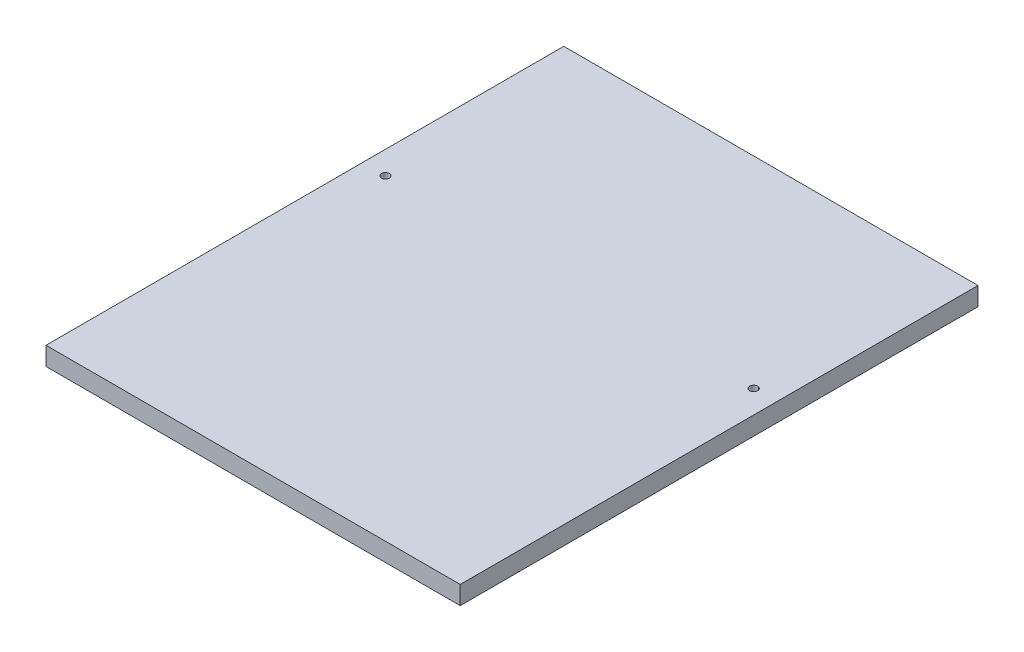
SolidWorks part; units mm, degrees
material "Сосна"
ref_plane "Front Plane" through (0, 0, 0) normal (0, 0, 1) x (1, 0, 0)
ref_plane "Top Plane" through (0, 0, 0) normal (0, 1, 0) x (1, 0, 0)
ref_plane "Right Plane" through (0, 0, 0) normal (1, 0, 0) x (0, 0, -1)
sketch "Эскиз2" plane through (0, 0, 0) normal (0, 1, 0) x (1, 0, 0)
  line L1 (0, 0) -> (360, 0)
  line L2 (0, 0) -> (0, 450)
  line L3 (0, 450) -> (360, 450)
  line L4 (360, 0) -> (360, 450)
  circle A0 centre (20, 275) radius 3.5
  circle A1 centre (340, 275) radius 3.5
  dimension "D3" = 7
  dimension "D4" = 20
  dimension "D5" = 20
  dimension "D6" = 175
  dimension "D7" = 320
  dimension "D1" = 450
  dimension "D2" = 360
extrude "Бобышка-Вытянуть1" add sketch "Эскиз2" along normal blind 16
